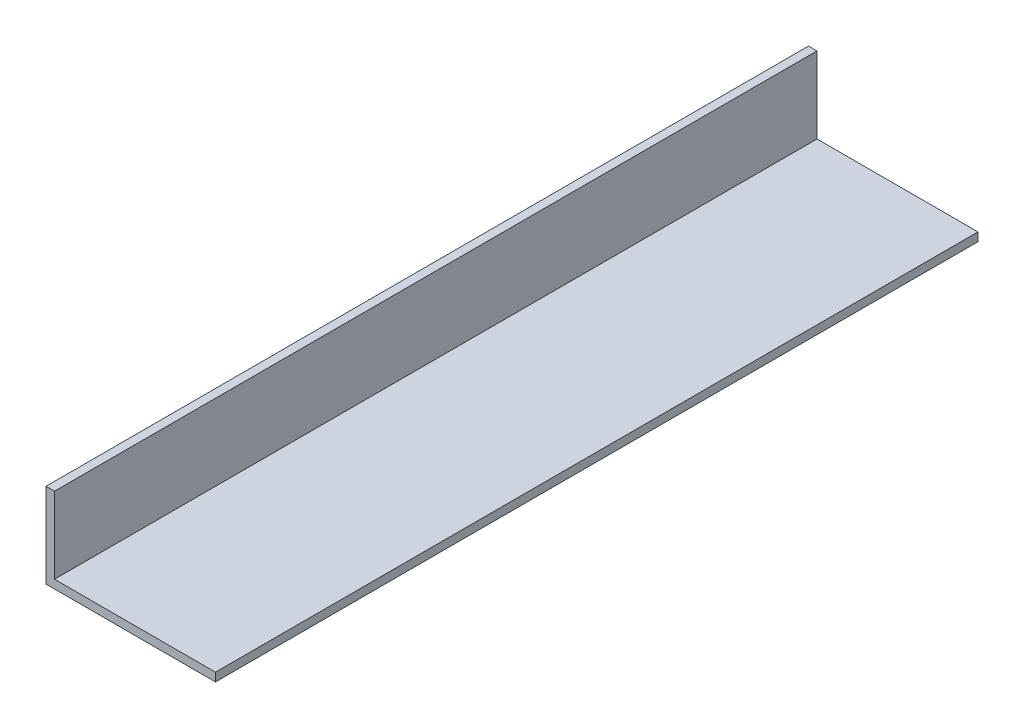
SolidWorks part; units mm, degrees
material "1060 Alloy"
ref_plane "Front Plane" through (0, 0, 0) normal (0, 0, 1) x (1, 0, 0)
ref_plane "Top Plane" through (0, 0, 0) normal (0, 1, 0) x (1, 0, 0)
ref_plane "Right Plane" through (0, 0, 0) normal (1, 0, 0) x (0, 0, -1)
sketch "Sketch1" plane through (0, 0, 0) normal (0, 0, 1) x (1, 0, 0)
  line L1 (-69.5798, 29.3277) -> (-67.5798, 29.3277)
  line L2 (-69.5798, 29.3277) -> (-69.5798, 11.3277)
  line L4 (-67.5798, 29.3277) -> (-67.5798, 11.3277)
  line L5 (-67.5798, 11.3277) -> (-29.5798, 11.3277)
  line L6 (-69.5798, 11.3277) -> (-69.5798, 9.3277)
  line L7 (-69.5798, 9.3277) -> (-29.5798, 9.3277)
  line L8 (-29.5798, 11.3277) -> (-29.5798, 9.3277)
  dimension "D1" = 20
  dimension "D2" = 40
  dimension "D3" = 2
  dimension "D4" = 2
extrude "Boss-Extrude1" add sketch "Sketch1" along normal blind 180
